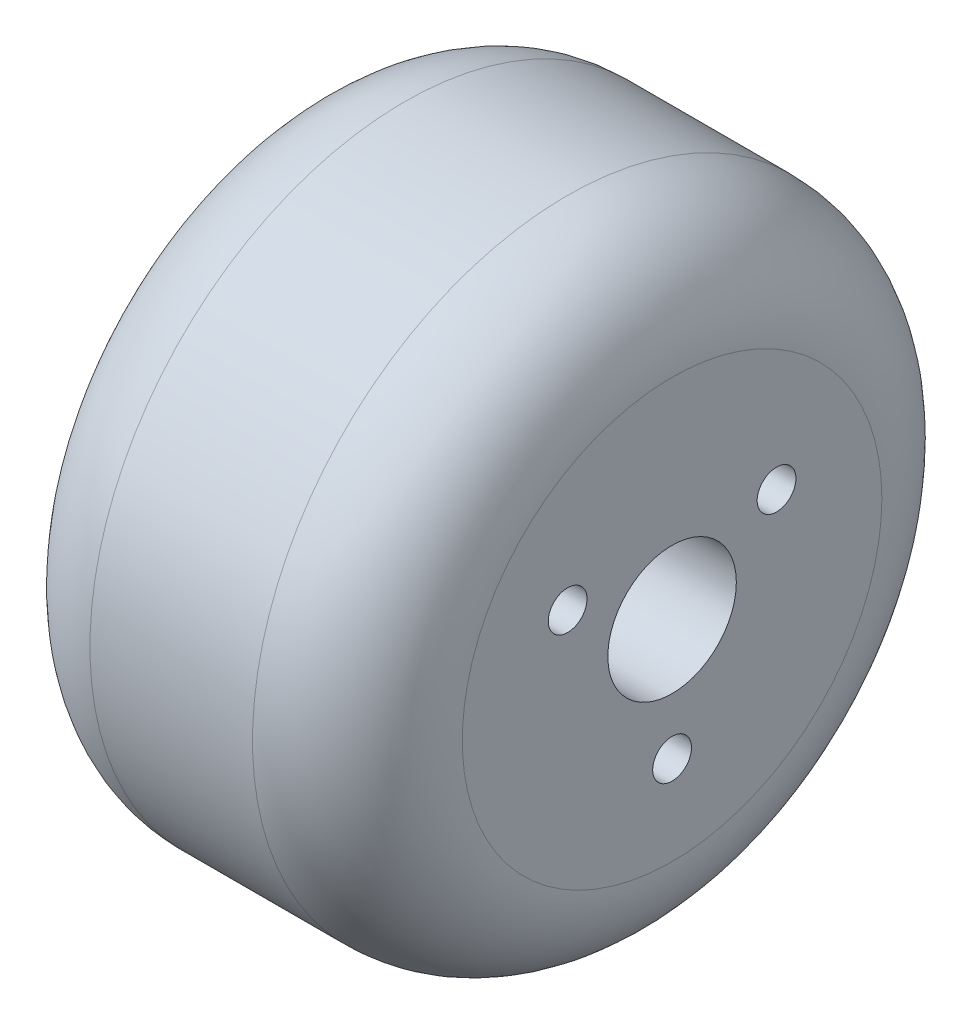
SolidWorks part; units mm, degrees
ref_plane "Front Plane" through (0, 0, 0) normal (0, 0, 1) x (1, 0, 0)
ref_plane "Top Plane" through (0, 0, 0) normal (0, 1, 0) x (1, 0, 0)
ref_plane "Right Plane" through (0, 0, 0) normal (1, 0, 0) x (0, 0, -1)
sketch "Sketch1" plane through (0, 0, 0) normal (1, 0, 0) x (0, 0, -1)
  circle A0 centre (0, 0) radius 30
  dimension "D1" = 60
extrude "Boss-Extrude1" add sketch "Sketch1" along normal blind 35.5
sketch "Sketch2" plane through (35.5, 0, 0) normal (1, 0, 0) x (0, 0, -1)
  line L0 (-9.9593, 5.75) -> (0, 0) construction
  line L1 (0, 0) -> (9.9593, 5.75) construction
  line L2 (0, 0) -> (0, -11.5) construction
  circle A0 centre (0, 0) radius 6.125
  circle A1 centre (0, 0) radius 11.5 construction
  circle A2 centre (-9.9593, 5.75) radius 1.85
  circle A3 centre (9.9593, 5.75) radius 1.85
  circle A4 centre (0, -11.5) radius 1.85
  dimension "D3" = 23
  dimension "D4" = 3.7
  dimension "D5" = 12.25
  dimension "D1" = 120
  dimension "D2" = 120
extrude "Cut-Extrude1" cut sketch "Sketch2" against normal through all
fillet "Fillet1" radius 10 2 edges at (0, 0, -30) (35.5, 0, -30)
